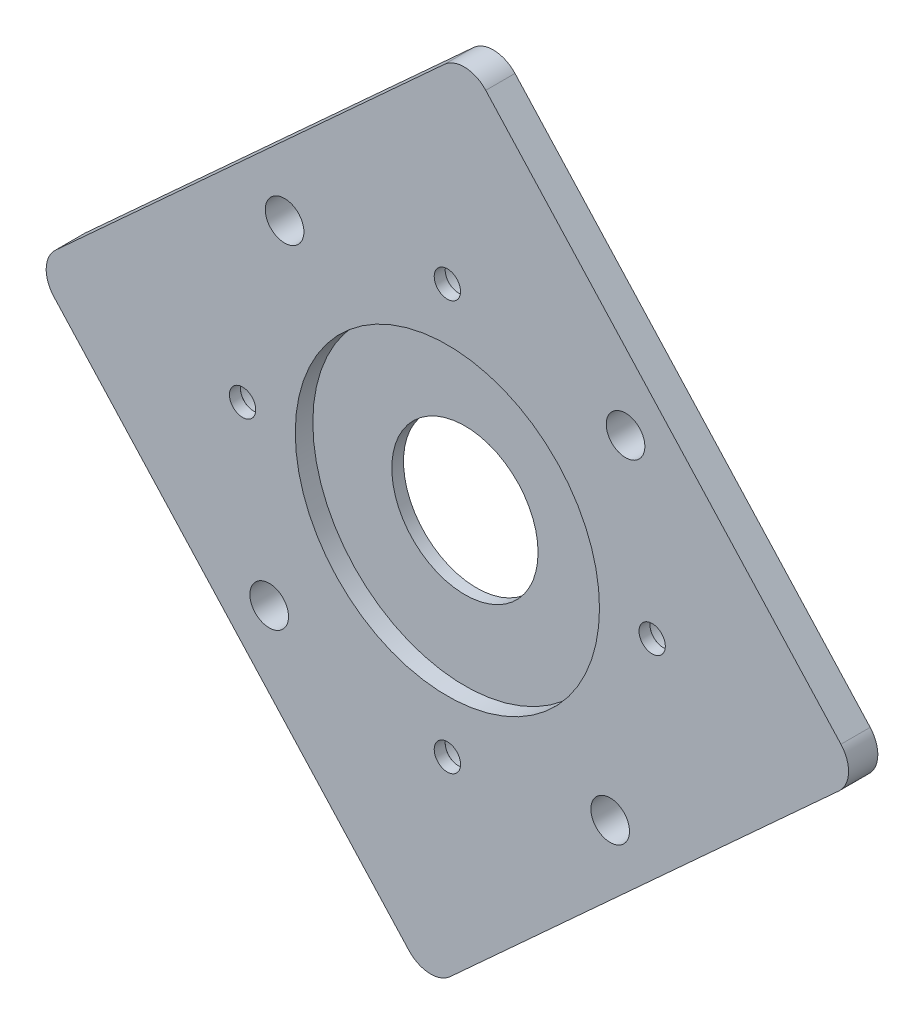
SolidWorks part; units mm, degrees
ref_plane "Plan de face" through (0, 0, 0) normal (0, 0, 1) x (1, 0, 0)
ref_plane "Plan de dessus" through (0, 0, 0) normal (0, 1, 0) x (1, 0, 0)
ref_plane "Plan de droite" through (0, 0, 0) normal (1, 0, 0) x (0, 0, -1)
sketch "Esquisse1" plane through (0, 0, 0) normal (0, 0, 1) x (1, 0, 0)
  circle A0 centre (0, 0) radius 50
  dimension "D1" = 100
extrude "Boss.-Extru.1" add sketch "Esquisse1" along normal blind 5
sketch "Esquisse2" plane through (0, 0, 5) normal (0, 0, 1) x (1, 0, 0)
  circle A1 centre (0, 0) radius 26
  dimension "D2" = 52
extrude "Enlèv. mat.-Extru.1" cut sketch "Esquisse2" against normal blind 3
sketch "Esquisse3" plane through (0, 0, 5) normal (0, 0, 1) x (1, 0, 0)
  circle A0 centre (0, 0) radius 12.5
  dimension "D1" = 25
extrude "Enlèv. mat.-Extru.2" cut sketch "Esquisse3" against normal through all
sketch "Esquisse4" plane through (0, 0, 0) normal (0, 0, -1) x (-1, 0, 0)
  circle A0 centre (0, 0) radius 35 construction
  dimension "D1" = 70
hole_wizard "Chambrage pour vis à tête ronde bombée M41" positions "Esquisse6" profile "Esquisse5" counterbore size "M4" standard "Ansi Metric" end condition through all
sketch "Esquisse6" plane through (0, 0, 0) normal (0, 0, -1) x (-1, 0, 0)
  circle A0 centre (0, 0) radius 35 construction
  point P0 (0, 35)
  point P4 (35, 0)
  point P6 (0, -35)
  point P8 (-35, 0)
sketch "Esquisse5" plane through (0, 35, 0) normal (1, 0, 0) x (0, 1, 0)
  line L0 (0, 0) -> (0, 5)
  line L1 (0, 5) -> (2.25, 5)
  line L2 (2.25, 3.125) -> (2.25, 5)
  line L3 (2.25, 3.125) -> (2.275, 3.1)
  line L4 (2.275, 3.1) -> (4.5, 3.1)
  line L5 (4.5, 3.1) -> (4.5, 0)
  line L7 (0, 0) -> (4.5, 0)
  line L9 (-2.25, 3.125) -> (-2.275, 3.1) construction
  line L11 (0, -6.35) -> (0, 107.95) construction
  dimension "Diamètre du perçage jusqu'au prochain" = 4.5
  dimension "Profondeur du perçage jusqu'au prochain" = 5
  dimension "Diamètre du chambrage" = 9
  dimension "Profondeur du chambrage" = 3.1
  dimension "Diamètre du fraisage milieu" = 4.55
  dimension "Angle du fraisage milieu" = 90
hole_wizard "Dégagement M62" positions "Esquisse10" profile "Esquisse9" hole size "M6" standard "JIS" end condition through all
sketch "Esquisse10" plane through (0, 0, 5) normal (0, 0, 1) x (1, 0, 0)
  point P0 (30.4527, 27.8244)
  point P2 (-27.8244, 30.4527)
  point P4 (-30.4527, -27.8244)
  point P6 (27.8244, -30.4527)
sketch "Esquisse9" plane through (30.4527, 27.8244, 5) normal (1, 0, 0) x (0, -1, 0)
  line L0 (0, 0) -> (0, 5)
  line L1 (0, 5) -> (3.3, 5)
  line L2 (3.3, 5) -> (3.3, 0)
  line L5 (3.3, 0) -> (0, 0)
  line L11 (0, -6.35) -> (0, 107.95) construction
  dimension "Diamètre du perçage jusqu'au prochain" = 6.6
  dimension "Profondeur du perçage jusqu'au prochain" = 5
sketch "Esquisse12" plane through (0, 0, 0) normal (0, 0, -1) x (-1, 0, 0)
  line L12 (-66.9476, -6.5584) -> (-0.5055, -67.2662)
  line L13 (6.5584, -66.9476) -> (67.2662, -0.5055)
  line L14 (66.9476, 6.5584) -> (0.5055, 67.2662)
  line L15 (-6.5584, 66.9476) -> (-67.2662, 0.5055)
  arc A13 (-0.5055, -67.2662) -> (6.5584, -66.9476) centre (2.8672, -63.575) ccw
  arc A14 (67.2662, -0.5055) -> (66.9476, 6.5584) centre (63.575, 2.8672) ccw
  arc A15 (0.5055, 67.2662) -> (-6.5584, 66.9476) centre (-2.8672, 63.575) ccw
  arc A16 (-67.2662, 0.5055) -> (-66.9476, -6.5584) centre (-63.575, -2.8672) ccw
extrude "Boss.-Extru.3" add sketch "Esquisse12" against normal blind 5
